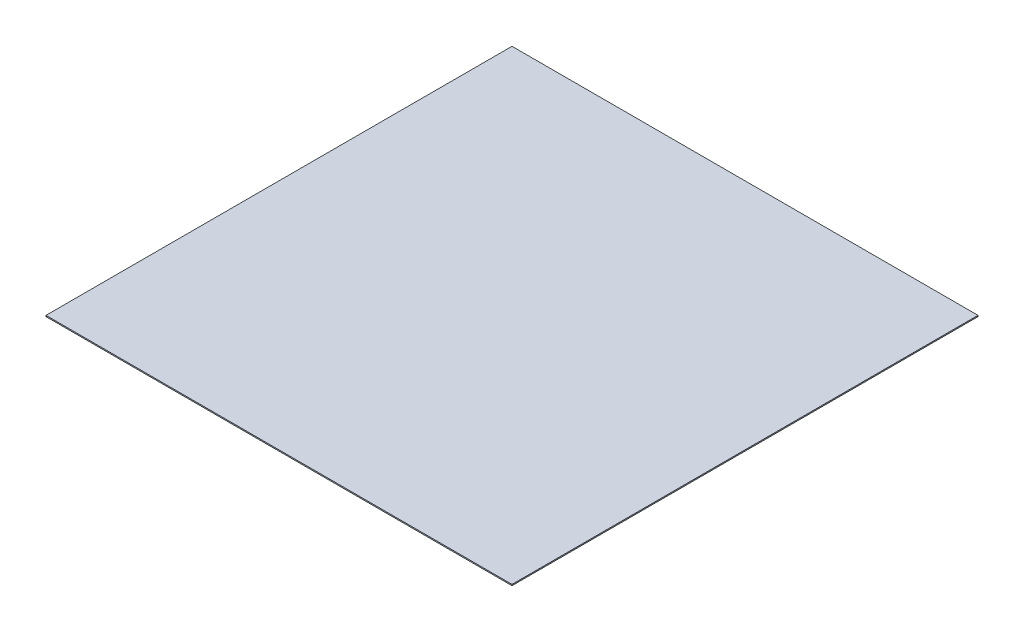
SolidWorks part; units mm, degrees
material "Beech"
ref_plane "Front Plane" through (0, 0, 0) normal (0, 0, 1) x (1, 0, 0)
ref_plane "Top Plane" through (0, 0, 0) normal (0, 1, 0) x (1, 0, 0)
ref_plane "Right Plane" through (0, 0, 0) normal (1, 0, 0) x (0, 0, -1)
sketch "Sketch2" plane through (0, 0, 0) normal (0, 1, 0) x (1, 0, 0)
  line L1 (-635, 635) -> (635, 635)
  line L2 (-635, 635) -> (-635, -635)
  line L3 (-635, -635) -> (635, -635)
  line L4 (635, 635) -> (635, -635)
  line L5 (-635, 635) -> (635, -635) construction
  line L6 (-635, -635) -> (635, 635) construction
  point P0 (0, 0)
  dimension "D1" = 1270
  dimension "D2" = 1270
extrude "Boss-Extrude1" add sketch "Sketch2" along normal blind 3.175
